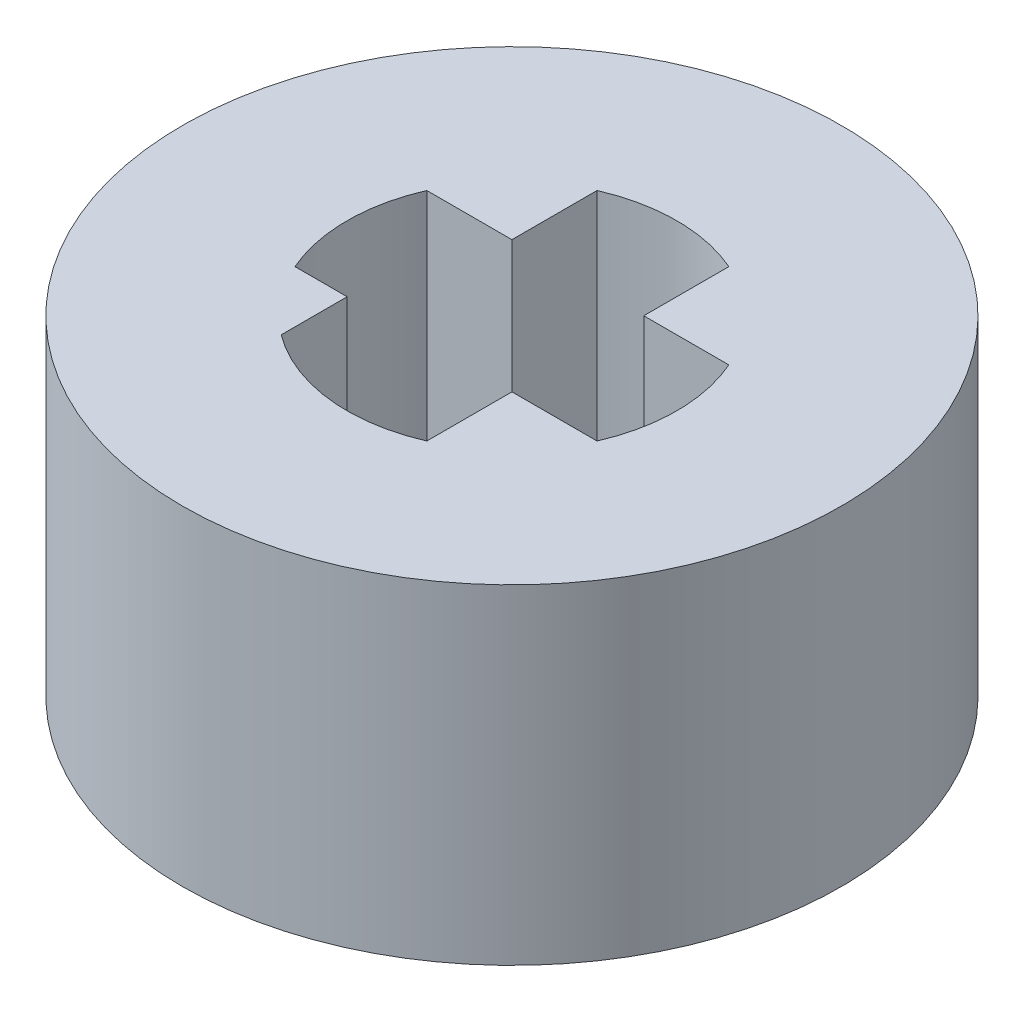
SolidWorks part; units mm, degrees
ref_plane "Alzado" through (0, 0, 0) normal (0, 0, 1) x (1, 0, 0)
ref_plane "Planta" through (0, 0, 0) normal (0, 1, 0) x (1, 0, 0)
ref_plane "Vista lateral" through (0, 0, 0) normal (1, 0, 0) x (0, 0, -1)
sketch "Sketch1" plane through (0, 0, 0) normal (0, 1, 0) x (1, 0, 0)
  line L0 (0, 9.1417) -> (0, -9.1417) construction
  line L1 (0, 0) -> (7.6067, 0) construction
  line L2 (-11.1724, 0) -> (0, 0) construction
  line L3 (1, -1) -> (1, -2.2913)
  line L4 (-1, 2.2913) -> (-1, 1)
  line L5 (1, -1) -> (2.2913, -1)
  line L6 (1, 2.2913) -> (1, 1)
  line L11 (-2.2913, -1) -> (-1.5, -1)
  line L12 (-2.2913, 1) -> (-1, 1)
  line L13 (1, 1) -> (2.2913, 1)
  line L14 (-1.5, -1) -> (-1.5, -2)
  circle A0 centre (0, 0) radius 5
  arc A1 (-2.2913, 1) -> (-2.2913, -1) centre (0, 0) ccw
  arc A2 (-1.5, -2) -> (1, -2.2913) centre (0, 0) ccw
  arc A3 (2.2913, -1) -> (2.2913, 1) centre (0, 0) ccw
  arc A4 (1, 2.2913) -> (-1, 2.2913) centre (0, 0) ccw
  dimension "D1" = 10
  dimension "D6" = 5
  dimension "D2" = 1
  dimension "D3" = 2
  dimension "D4" = 2
  dimension "D5" = 1
extrude "Boss-Extrude1" add sketch "Sketch1" along normal blind 5
